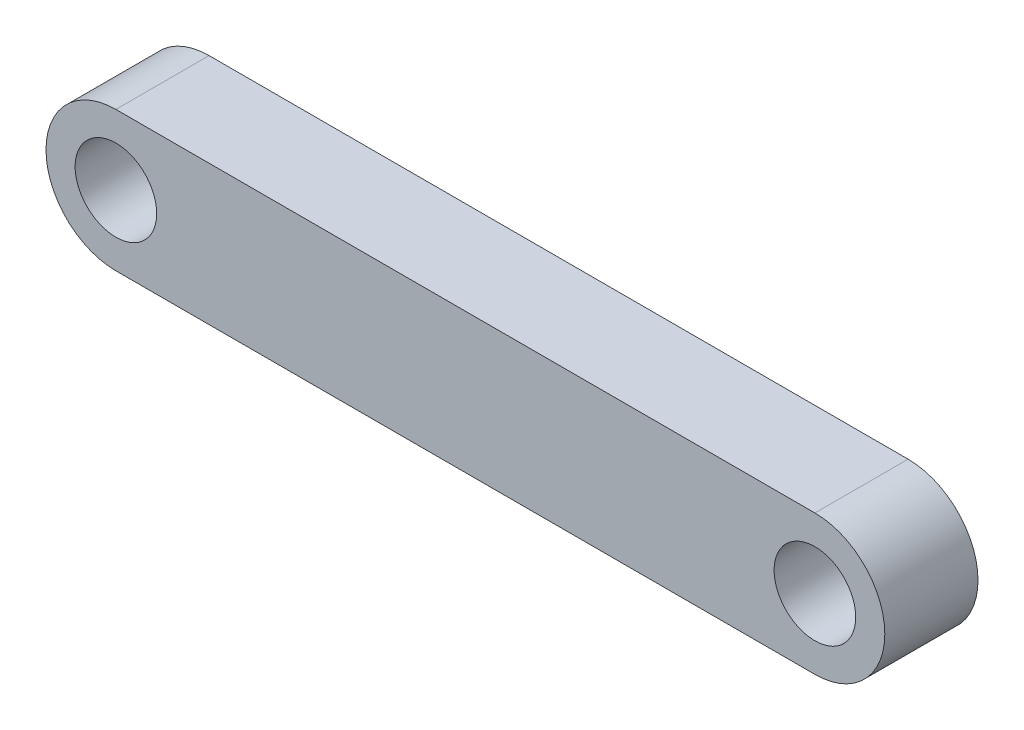
SolidWorks part; units mm, degrees
ref_plane "前视基准面" through (0, 0, 0) normal (0, 0, 1) x (1, 0, 0)
ref_plane "上视基准面" through (0, 0, 0) normal (0, 1, 0) x (1, 0, 0)
ref_plane "右视基准面" through (0, 0, 0) normal (1, 0, 0) x (0, 0, -1)
sketch "草图1" plane through (0, 0, 0) normal (0, 0, 1) x (1, 0, 0)
  line L0 (0, 0) -> (30, 0) construction
  line L1 (0, -3) -> (30, -3)
  line L2 (0, 3) -> (30, 3)
  arc A0 (0, -3) -> (0, 3) centre (0, 0) cw
  arc A1 (30, -3) -> (30, 3) centre (30, 0) ccw
  circle A2 centre (0, 0) radius 1.75
  circle A3 centre (30, 0) radius 1.75
  dimension "D4" = 3.5
  dimension "D5" = 3.5
  dimension "D1" = 30
  dimension "D2" = 3
  dimension "D3" = 3
extrude "凸台-拉伸1" add sketch "草图1" along normal blind 4
